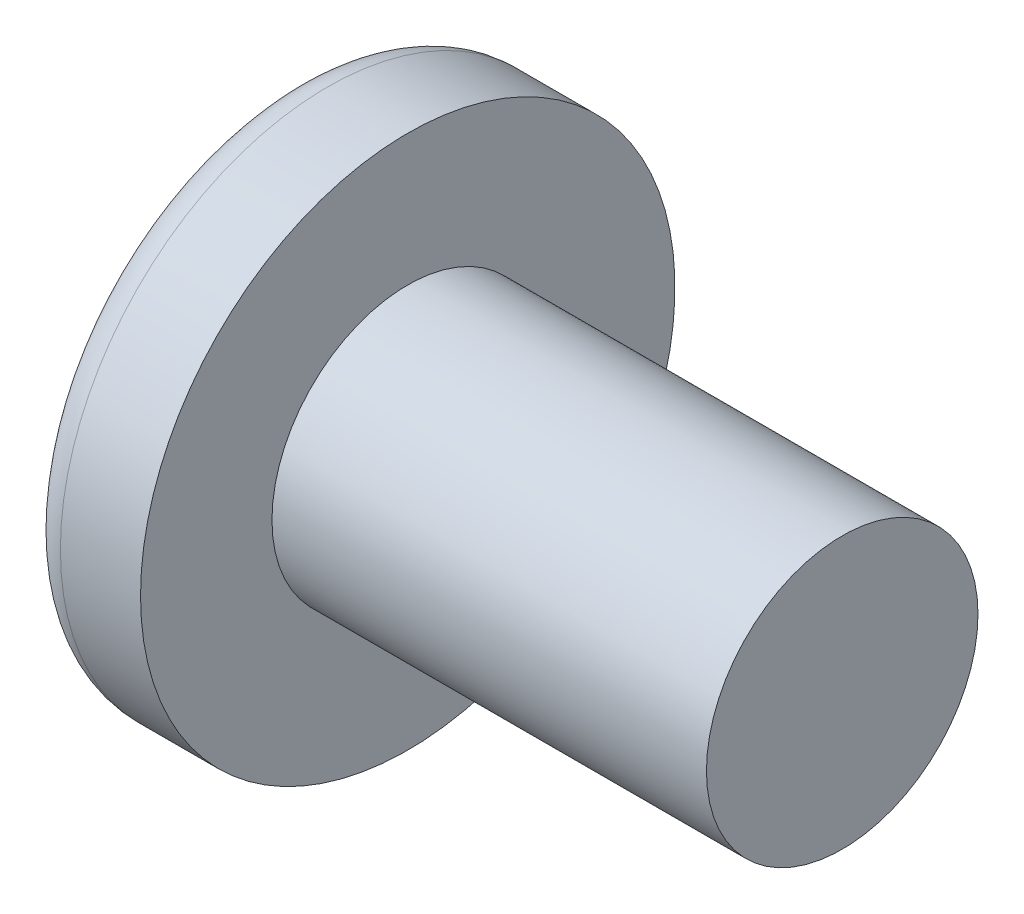
SolidWorks part; units mm, degrees
ref_plane "Plane1" through (0, 0, 0) normal (0, 0, 1) x (1, 0, 0)
ref_plane "Plane2" through (0, 0, 0) normal (0, 1, 0) x (1, 0, 0)
ref_plane "Plane3" through (0, 0, 0) normal (1, 0, 0) x (0, 0, -1)
sketch "BodySke" plane through (0, 0, 0) normal (0, 0, 1) x (1, 0, 0)
  line L0 (5.5372, 3.9688) -> (5.5372, 7.8105)
  line L1 (6.242, 6.35) -> (6.242, -3.175) construction
  line L2 (-25.4, 0) -> (127, 0) construction
  line L3 (18.2372, 0) -> (0, 0)
  line L4 (5.5372, 3.9688) -> (18.2372, 3.9688)
  line L5 (18.2372, 3.9688) -> (18.2372, 0)
  line L6 (3.1947, 7.8105) -> (5.5372, 7.8105)
  line L7 (5.5372, -3.9688) -> (18.2372, -3.9688) construction
  line L8 (5.5372, 6.35) -> (5.5372, -3.175) construction
  arc A0 (2.3682, 7.3853) -> (0, 0) centre (12.7, 0) ccw
  arc A2 (2.3682, 7.3853) -> (3.1947, 7.8105) centre (3.1947, 6.7945) cw
  dimension "Head_fillet_rad" = 1.016
  dimension "Head_crown_rad" = 12.7
  dimension "Head_ht" = 5.5372
  dimension "Diameter" = 7.9375
  dimension "Length" = 12.7
  dimension "Head_dia" = 15.621
  dimension "Advance" = 1.4097
  dimension "Thread_nom" = 12.7
revolve "Base-Revolve" add sketch "BodySke" angle 360 about L2
cosmetic thread "ThreadCosmetic" [suppressed] parameters "Thread_length"=11.2903, "Thread_minor"=6.2586
sketch "Sketch3" plane through (0, 0, 0) normal (1, 0, 0) x (0, 0, -1)
  line L0 (0.8763, -5.0292) -> (-0.8763, -5.0292)
  line L1 (0.8763, -5.0292) -> (0.8763, 5.0292)
  line L2 (-0.8763, 5.0292) -> (0.8763, 5.0292)
  line L3 (-0.8763, 5.0292) -> (-0.8763, -5.0292)
  dimension "D1" = 5.0292
  dimension "Cross_dia" = 10.0584
  dimension "D2" = 0.8763
  dimension "Cross_width" = 1.7526
ref_plane "Plane4" through (5.8674, 0, 0) normal (1, 0, 0) x (0, 0, -1)
sketch "Sketch4" plane through (5.8674, 0, 0) normal (1, 0, 0) x (0, 0, -1)
  line L0 (0.4381, -0.4381) -> (-0.4381, -0.4382)
  line L1 (0.4381, -0.4381) -> (0.4381, 0.4381)
  line L2 (-0.4381, 0.4381) -> (0.4381, 0.4381)
  line L3 (-0.4381, 0.4381) -> (-0.4381, -0.4382)
  dimension "D1" = 0.8763
  dimension "D2" = 0.8763
  dimension "D3" = 0.4381
  dimension "D4" = 0.4381
loft "Cut-Loft1" cut profiles "Sketch3", "Sketch4"
pattern_circular "CirPattern1" count 2 every 90 about axis through (0, 0, 0) along (1, 0, 0) of "Cut-Loft1"
sketch "ThdSchSke" plane through (0, 0, 0) normal (0, 0, 1) x (1, 0, 0)
  line L0 (6.9469, -3.1293) -> (6.3591, -3.9688)
  line L1 (6.9469, -3.1293) -> (7.5347, -3.9688)
  line L2 (7.5347, -3.9688) -> (7.5347, -4.9609)
  line L3 (-3.175, 0) -> (5.1513, 0) construction
  line L5 (7.5347, -4.9609) -> (6.3591, -4.9609)
  line L6 (6.3591, -4.9609) -> (6.3591, -3.9688)
  dimension "Thread_minor" = 6.2586
  dimension "Diameter" = 7.9375
  dimension "Start" = 6.9469
  dimension "SideAngle" = 55
  dimension "VeeAngle" = 70
  dimension "Overcut" = 9.9219
revolve "ThreadSchematic" [suppressed] cut sketch "ThdSchSke" angle 360 about L3
pattern_linear "ThdSchPat" [suppressed]
equation "\"D1@Sketch3\" = \"Cross_dia@Sketch3\" / 2"
equation "\"D2@Sketch3\" = \"Cross_width@Sketch3\" / 2"
equation "\"D1@Sketch4\" = \"Cross_width@Sketch3\" *.5"
equation "\"D2@Sketch4\" = \"D1@Sketch4\""
equation "\"D3@Sketch4\" = \"D1@Sketch4\" / 2"
equation "\"D4@Sketch4\" = \"D2@Sketch4\" / 2"
equation "\"Thread_length@ThreadCosmetic\" = ((sgn( (\"Length@BodySke\" - \"Advance@BodySke\" ) - \"Thread_nom@BodySke\" )-1)*( (\"Length@BodySke\" - \"Advance@BodySke\" ) - \"Thread_nom@BodySke\" ))/-2+ \"Thread_nom@BodySke\""
equation "\"Thread_minor@ThdSchSke\" = \"Thread_minor@ThreadCosmetic\""
equation "\"Diameter@ThdSchSke\" = \"Diameter@BodySke\""
equation "\"Overcut@ThdSchSke\" = \"Diameter@BodySke\" * 1.25"
equation "\"Start@ThdSchSke\" = \"Head_ht@BodySke\" + \"Length@BodySke\" - \"Thread_length@ThreadCosmetic\"  '---Non-countersunk---"
equation "\"Num_threads@ThdSchPat\" = int( \"Thread_length@ThreadCosmetic\" / \"Advance@BodySke\" + 0.999 )  + 1"
equation "\"Advance@ThdSchPat\" = \"Thread_length@ThreadCosmetic\" /  (\"Num_threads@ThdSchPat\" - 1) 'relax it"
